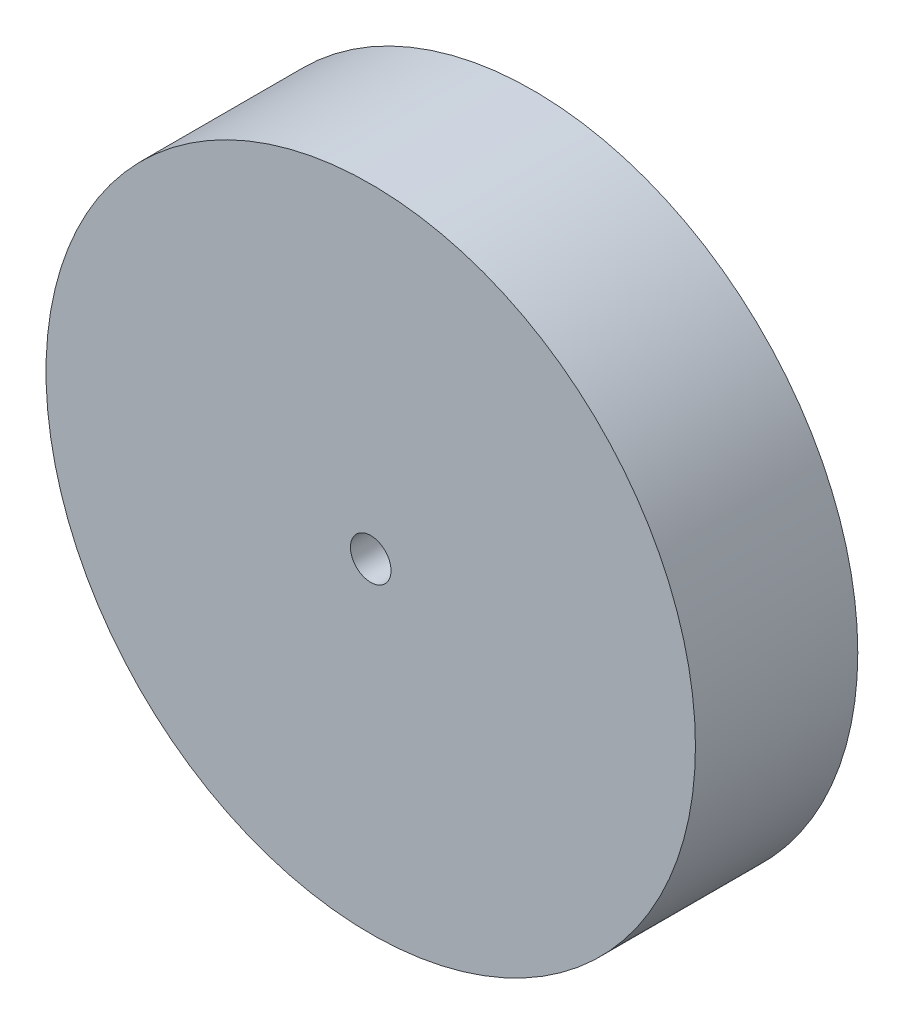
SolidWorks part; units mm, degrees
ref_plane "Front Plane" through (0, 0, 0) normal (0, 0, 1) x (1, 0, 0)
ref_plane "Top Plane" through (0, 0, 0) normal (0, 1, 0) x (1, 0, 0)
ref_plane "Right Plane" through (0, 0, 0) normal (1, 0, 0) x (0, 0, -1)
sketch "Sketch1" plane through (0, 0, 0) normal (0, 0, 1) x (1, 0, 0)
  circle A0 centre (0, 0) radius 101.6
  circle A1 centre (0, 0) radius 6.35
  dimension "D1" = 203.2
extrude "Boss-Extrude1" add sketch "Sketch1" along normal blind 50.8
